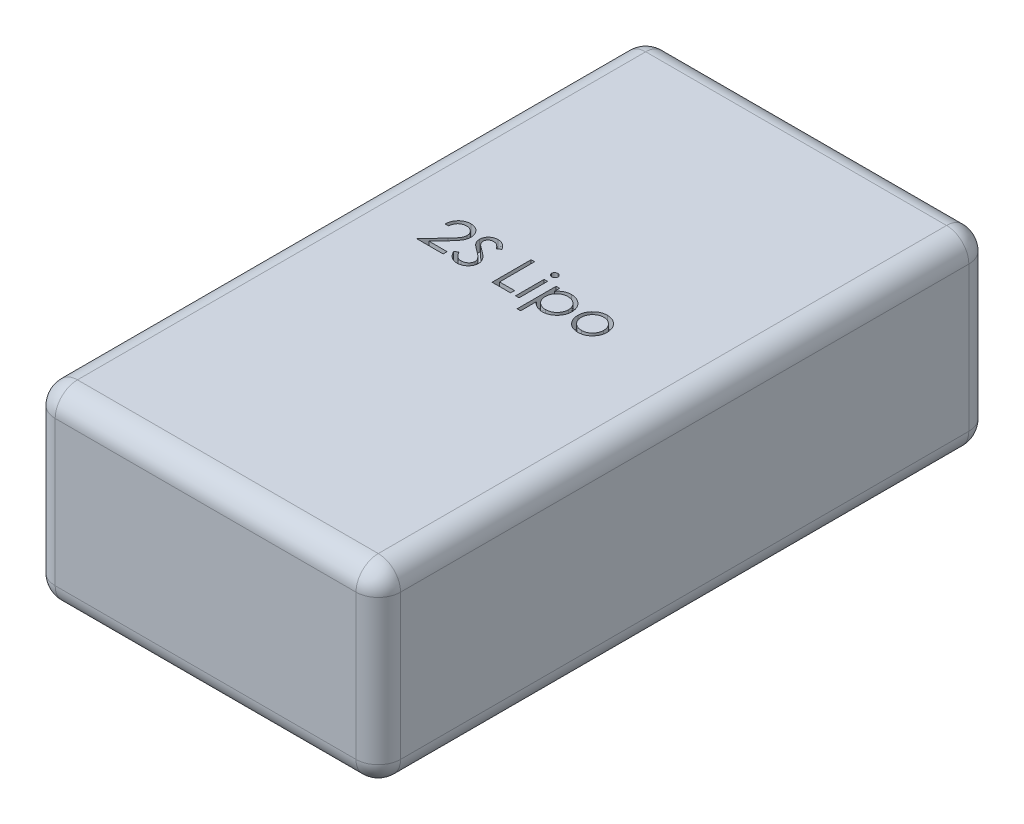
SolidWorks part; units mm, degrees
ref_plane "Front Plane" through (0, 0, 0) normal (0, 0, 1) x (1, 0, 0)
ref_plane "Top Plane" through (0, 0, 0) normal (0, 1, 0) x (1, 0, 0)
ref_plane "Right Plane" through (0, 0, 0) normal (1, 0, 0) x (0, 0, -1)
sketch "Sketch1" plane through (0, 0, 0) normal (0, 1, 0) x (1, 0, 0)
  line L1 (0, 0) -> (31, 0)
  line L2 (0, 0) -> (0, -55)
  line L3 (0, -55) -> (31, -55)
  line L4 (31, 0) -> (31, -55)
  dimension "D1" = 55
  dimension "D2" = 31
extrude "Boss-Extrude1" add sketch "Sketch1" along normal blind 17 contours L2 L3 L4 L1
sketch "Sketch2" plane through (0, 17, 0) normal (0, 1, 0) x (1, 0, 0)
  text T0 "2S Lipo"
extrude "Cut-Extrude1" cut sketch "Sketch2" against normal blind 1
fillet "Fillet1" radius 2 12 edges at (15.5, 17, 55) (15.5, 0, 55) (0, 0, 27.5) (31, 0, 27.5) (0, 17, 27.5) (31, 17, 27.5) (15.5, 0, 0) (15.5, 17, 0) (0, 8.5, 0) (31, 8.5, 0) (31, 8.5, 55) (0, 8.5, 55)
